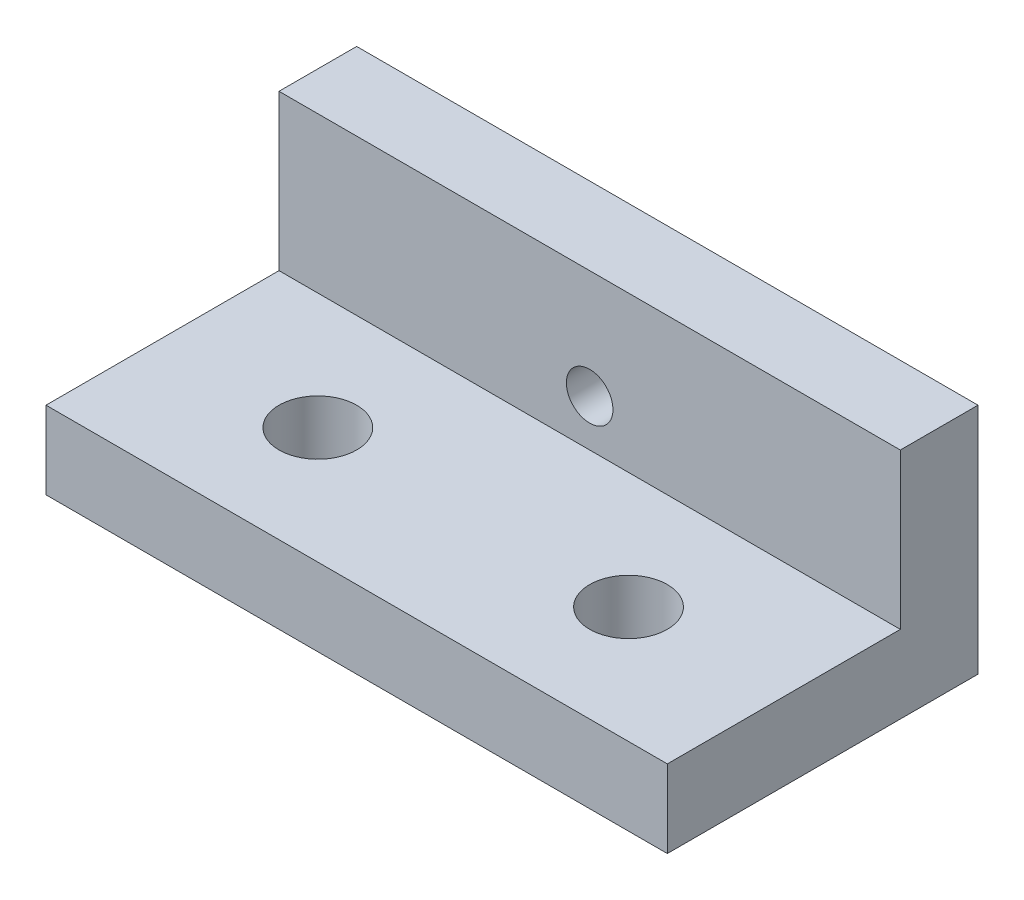
SolidWorks part; units mm, degrees
ref_plane "Front Plane" through (0, 0, 0) normal (0, 0, 1) x (1, 0, 0)
ref_plane "Top Plane" through (0, 0, 0) normal (0, 1, 0) x (1, 0, 0)
ref_plane "Right Plane" through (0, 0, 0) normal (1, 0, 0) x (0, 0, -1)
sketch "Sketch1" plane through (0, 0, 0) normal (0, 1, 0) x (1, 0, 0)
  line L1 (0, 0) -> (25.4, 0)
  line L2 (0, 0) -> (0, 12.7)
  line L3 (0, 12.7) -> (25.4, 12.7)
  line L4 (25.4, 0) -> (25.4, 12.7)
  dimension "D1" = 25.4
  dimension "D2" = 12.7
extrude "Boss-Extrude1" add sketch "Sketch1" along normal blind 3.175
sketch "Sketch2" plane through (0, 3.175, 0) normal (0, 1, 0) x (1, 0, 0)
  line L0 (25.4, 0) -> (25.4, 12.7) construction
  line L1 (0, 12.7) -> (25.4, 12.7)
  line L2 (0, 12.7) -> (0, 9.525)
  line L3 (0, 9.525) -> (25.4, 9.525)
  line L4 (25.4, 12.7) -> (25.4, 9.525)
  dimension "D1" = 3.175
extrude "Boss-Extrude2" add sketch "Sketch2" along normal blind 6.35
sketch "Sketch3" plane through (0, 0, -12.7) normal (0, 0, -1) x (-1, 0, 0)
  line L0 (-12.7, 9.525) -> (-12.7, 0) construction
  line L1 (-25.4, 9.525) -> (0, 9.525) construction
  line L2 (-25.4, 0) -> (0, 0) construction
  circle A0 centre (-12.7, 5.08) radius 0.9525
  dimension "D1" = 1.905
  dimension "D2" = 4.445
extrude "Cut-Extrude1" cut sketch "Sketch3" against normal through all
sketch "Sketch4" plane through (0, 3.175, 0) normal (0, 1, 0) x (1, 0, 0)
  line L0 (12.7, 9.525) -> (12.7, 0) construction
  line L1 (0, 9.525) -> (25.4, 9.525) construction
  line L2 (0, 0) -> (25.4, 0) construction
  circle A0 centre (6.35, 4.7625) radius 1.5875
  circle A1 centre (19.05, 4.7625) radius 1.5875
  point P8 (12.7, 4.7625)
  dimension "D1" = 3.175
  dimension "D2" = 6.35
extrude "Cut-Extrude2" cut sketch "Sketch4" against normal through all
